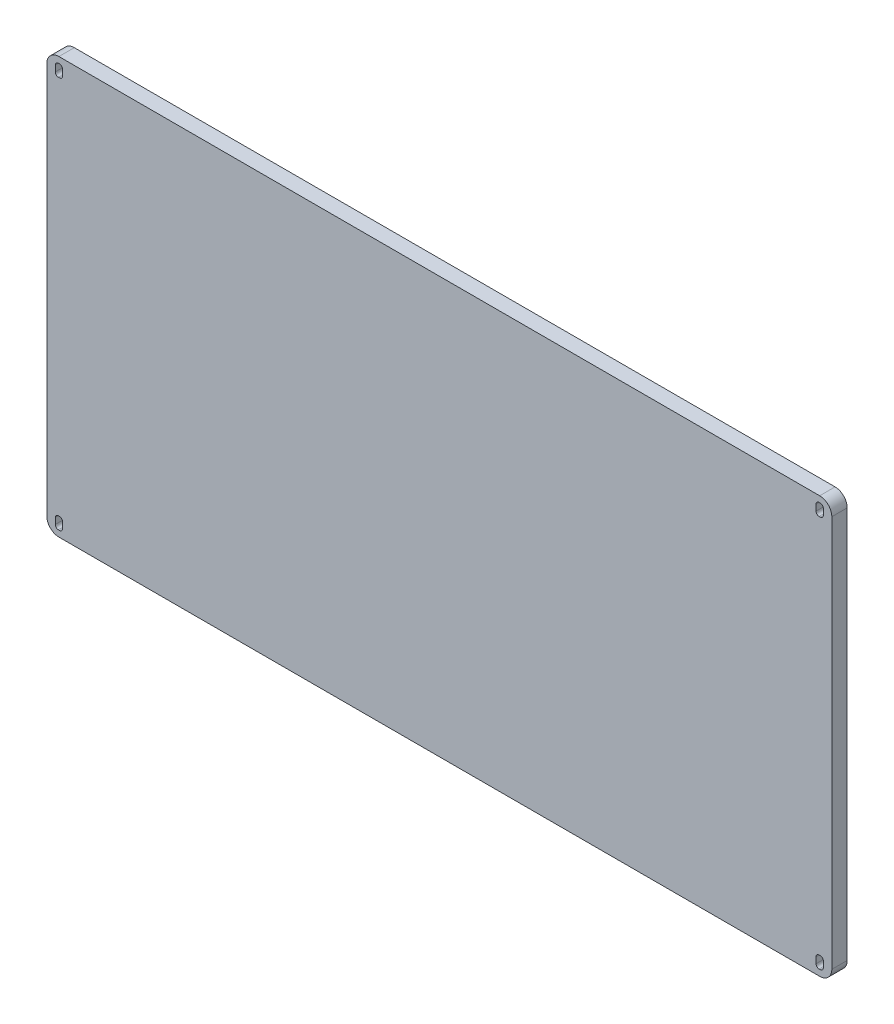
SolidWorks part; units mm, degrees
ref_plane "Front Plane" through (0, 0, 0) normal (0, 0, 1) x (1, 0, 0)
ref_plane "Top Plane" through (0, 0, 0) normal (0, 1, 0) x (1, 0, 0)
ref_plane "Right Plane" through (0, 0, 0) normal (1, 0, 0) x (0, 0, -1)
sketch "Sketch1" plane through (0, 0, 0) normal (0, 0, 1) x (1, 0, 0)
  line L0 (217.467, -94.146) -> (216.467, -94.146)
  line L1 (-420.733, 244.262) -> (226.967, 244.262)
  line L2 (-420.733, 244.262) -> (-420.733, -99.146)
  line L3 (-420.733, -99.146) -> (226.967, -99.146)
  line L4 (226.967, 244.262) -> (226.967, -99.146)
  line L5 (213.967, -91.646) -> (213.967, -86.646)
  line L6 (217.467, -84.146) -> (216.467, -84.146)
  line L7 (219.967, -91.646) -> (219.967, -86.646)
  line L8 (-410.733, 244.262) -> (-410.733, -99.146)
  line L9 (-410.733, 244.262) -> (236.967, 244.262)
  line L11 (-410.733, -99.146) -> (236.967, -99.146)
  line L12 (-410.233, -94.146) -> (-411.233, -94.146)
  line L13 (-413.733, -91.646) -> (-413.733, -86.646)
  line L14 (-410.233, -84.146) -> (-411.233, -84.146)
  line L15 (-407.733, -91.646) -> (-407.733, -86.646)
  line L16 (-410.233, 229.262) -> (-411.233, 229.262)
  line L17 (-413.733, 231.762) -> (-413.733, 236.762)
  line L18 (-410.233, 239.262) -> (-411.233, 239.262)
  line L19 (-407.733, 231.762) -> (-407.733, 236.762)
  line L20 (217.467, 229.262) -> (216.467, 229.262)
  line L21 (213.967, 231.762) -> (213.967, 236.762)
  line L22 (217.467, 239.262) -> (216.467, 239.262)
  line L23 (219.967, 231.762) -> (219.967, 236.762)
  line L24 (216.967, -84.146) -> (216.967, -94.146) construction
  line L25 (213.967, -89.146) -> (219.967, -89.146) construction
  line L26 (-410.733, -84.146) -> (-410.733, -94.146) construction
  line L27 (-413.733, -89.146) -> (-407.733, -89.146) construction
  line L28 (-410.733, 239.262) -> (-410.733, 229.262) construction
  line L29 (-413.733, 234.262) -> (-407.733, 234.262) construction
  line L30 (236.967, 244.262) -> (236.967, -99.146) [skipped]
  arc A0 (216.467, -94.146) -> (213.967, -91.646) centre (216.467, -91.646) cw
  arc A1 (216.467, -84.146) -> (213.967, -86.646) centre (216.467, -86.646) ccw
  arc A2 (219.967, -86.646) -> (217.467, -84.146) centre (217.467, -86.646) ccw
  arc A3 (217.467, -94.146) -> (219.967, -91.646) centre (217.467, -91.646) ccw
  arc A4 (-411.233, -94.146) -> (-413.733, -91.646) centre (-411.233, -91.646) cw
  arc A5 (-411.233, -84.146) -> (-413.733, -86.646) centre (-411.233, -86.646) ccw
  arc A6 (-407.733, -86.646) -> (-410.233, -84.146) centre (-410.233, -86.646) ccw
  arc A7 (-410.233, -94.146) -> (-407.733, -91.646) centre (-410.233, -91.646) ccw
  arc A8 (-411.233, 229.262) -> (-413.733, 231.762) centre (-411.233, 231.762) cw
  arc A9 (-411.233, 239.262) -> (-413.733, 236.762) centre (-411.233, 236.762) ccw
  arc A10 (-407.733, 236.762) -> (-410.233, 239.262) centre (-410.233, 236.762) ccw
  arc A11 (-410.233, 229.262) -> (-407.733, 231.762) centre (-410.233, 231.762) ccw
  arc A12 (216.467, 229.262) -> (213.967, 231.762) centre (216.467, 231.762) cw
  arc A13 (216.467, 239.262) -> (213.967, 236.762) centre (216.467, 236.762) ccw
  arc A14 (219.967, 236.762) -> (217.467, 239.262) centre (217.467, 236.762) ccw
  arc A15 (217.467, 229.262) -> (219.967, 231.762) centre (217.467, 231.762) ccw
  point P16 (216.967, -84.146)
  point P17 (213.967, -89.146)
  point P62 (216.967, -89.146)
  point P67 (-410.733, -89.146)
  dimension "D4" = 2.5
  dimension "D13" = 2.5
  dimension "D1" = 647.7
  dimension "D2" = 343.408
  dimension "D3" = 10
  dimension "D5" = 6
  dimension "D9" = 10
  dimension "D10" = 10
  dimension "10mm" = 10
  dimension "10" = 10
  dimension "D11" = 244.262
  dimension "D12" = 226.967
  dimension "D14" = 231.762
  dimension "D6" = 2
  dimension "D7" = 2
  dimension "D8" = 2
extrude "Boss-Extrude3" add sketch "Sketch1" along normal blind 12.7 contours A11 L16 L8 L14 A6 L15 A7 L12 L3 L4 L1 L18 A10 L19 A15 L20 A12 L21 A13 L22 A14 L23 A3 L0 A0 L5 A1 L6 A2 L7 | A9 L18 L8 L1 L2 L3 L12 A4 L13 A5 L14 L16 A8 L17
fillet "Fillet1" radius 10 4 edges at (226.967, 244.262, 6.35) (226.967, -99.146, 6.35) (-420.733, -99.146, 6.35) (-420.733, 244.262, 6.35)
